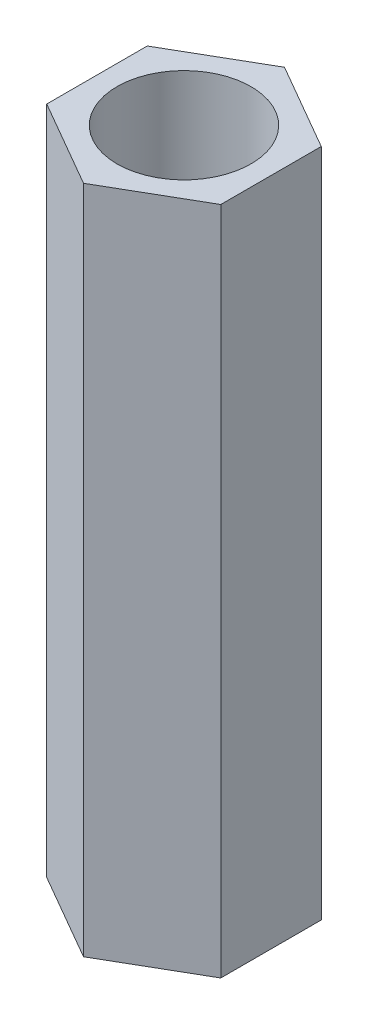
SolidWorks part; units mm, degrees
material "黄铜"
ref_plane "前视基准面" through (0, 0, 0) normal (0, 0, 1) x (1, 0, 0)
ref_plane "上视基准面" through (0, 0, 0) normal (0, 1, 0) x (1, 0, 0)
ref_plane "右视基准面" through (0, 0, 0) normal (1, 0, 0) x (0, 0, -1)
other "Configuration Table"
sketch "草图1" plane through (0, 0, 0) normal (0, 1, 0) x (1, 0, 0)
  line L1 (0, 3) -> (-2.5981, 1.5)
  line L2 (-2.5981, 1.5) -> (-2.5981, -1.5)
  line L3 (-2.5981, -1.5) -> (0, -3)
  line L4 (0, -3) -> (2.5981, -1.5)
  line L5 (2.5981, -1.5) -> (2.5981, 1.5)
  line L6 (2.5981, 1.5) -> (0, 3)
  circle A0 centre (0, 0) radius 2
  circle A1 centre (0, 0) radius 2.5981 construction
  dimension "D1" = 4
  dimension "D2" = 6
extrude "凸台-拉伸1" add sketch "草图1" along normal blind 20
